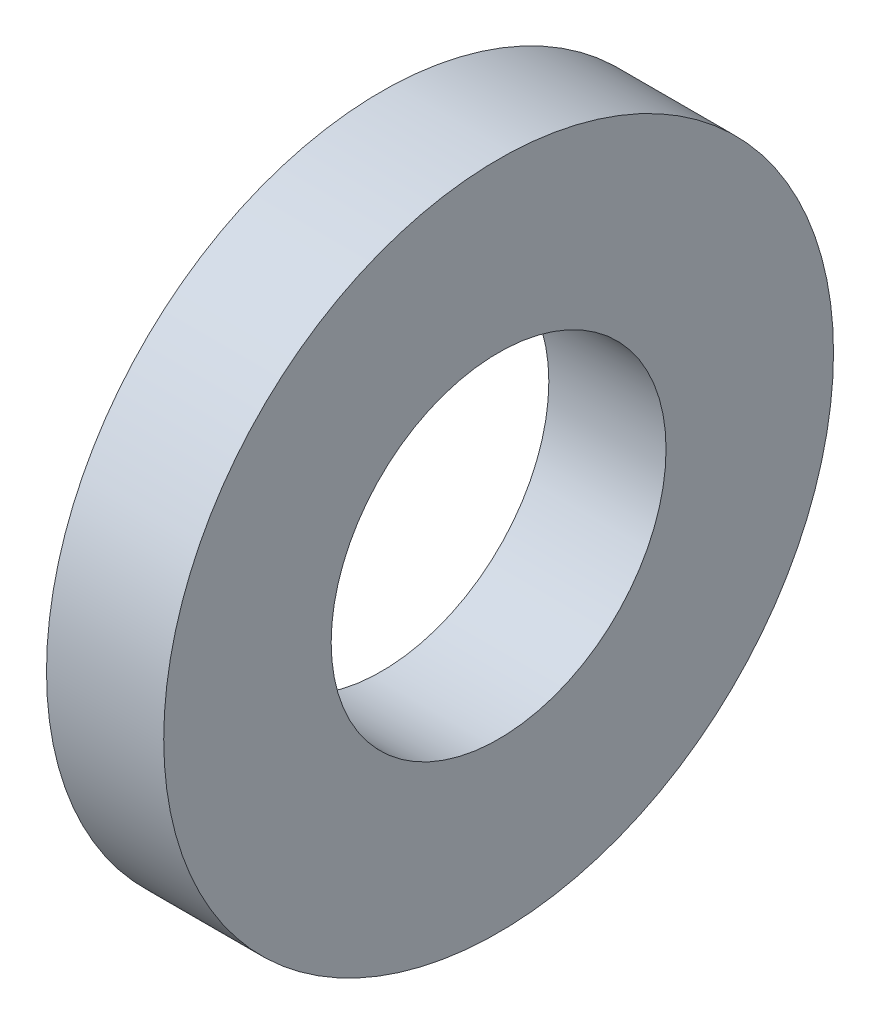
SolidWorks part; units mm, degrees
ref_plane "Front Plane" through (0, 0, 0) normal (0, 0, 1) x (1, 0, 0)
ref_plane "Top Plane" through (0, 0, 0) normal (0, 1, 0) x (1, 0, 0)
ref_plane "Right Plane" through (0, 0, 0) normal (1, 0, 0) x (0, 0, -1)
sketch "Sketch1" plane through (0, 0, 0) normal (1, 0, 0) x (0, 0, -1)
  circle A0 centre (0, 0) radius 5
  circle A1 centre (0, 0) radius 10
  dimension "D1" = 20
  dimension "D2" = 10
extrude "Boss-Extrude1" add sketch "Sketch1" along normal blind 3.5
